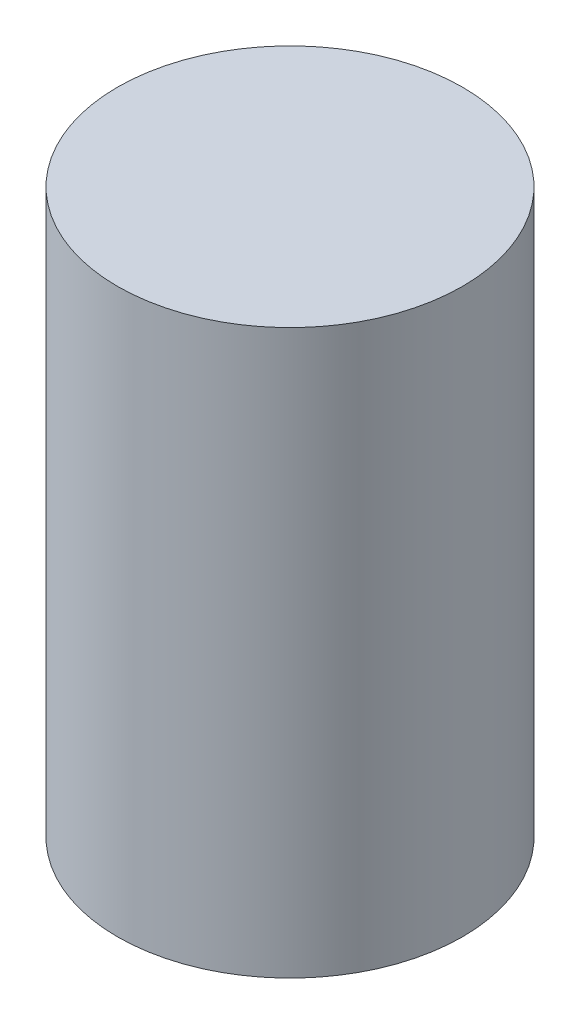
SolidWorks part; units mm, degrees
ref_plane "Front Plane" through (0, 0, 0) normal (0, 0, 1) x (1, 0, 0)
ref_plane "Top Plane" through (0, 0, 0) normal (0, 1, 0) x (1, 0, 0)
ref_plane "Right Plane" through (0, 0, 0) normal (1, 0, 0) x (0, 0, -1)
sketch "Sketch1" plane through (0, 0, 0) normal (0, 1, 0) x (1, 0, 0)
  circle A0 centre (0, 0) radius 2.45
  dimension "D1" = 4.9
extrude "Boss-Extrude1" add sketch "Sketch1" along normal blind 8 contours A0
sketch "Sketch2" plane through (0, 0, 0) normal (0, -1, 0) x (1, 0, 0)
  circle A0 centre (0, 0) radius 1.65
  dimension "D1" = 3.3
extrude "Cut-Extrude1" cut sketch "Sketch2" against normal blind 7
